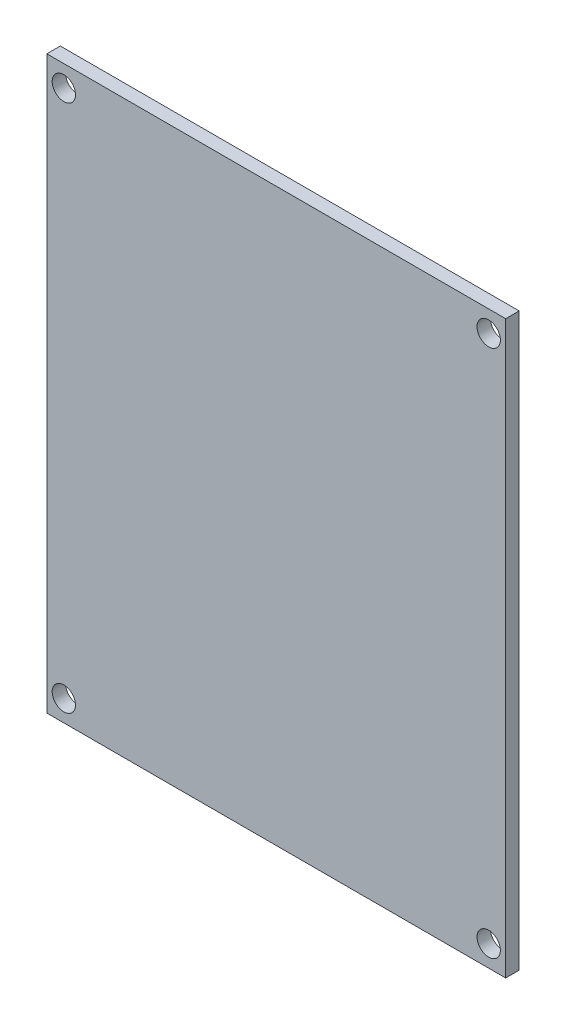
SolidWorks part; units mm, degrees
ref_plane "Front" through (0, 0, 0) normal (0, 0, 1) x (1, 0, 0)
ref_plane "Top" through (0, 0, 0) normal (0, 1, 0) x (1, 0, 0)
ref_plane "Right" through (0, 0, 0) normal (1, 0, 0) x (0, 0, -1)
sketch "Sketch1" plane through (0, 0, 0) normal (0, 0, 1) x (1, 0, 0)
  line L1 (-60, -67.25) -> (60, -67.25)
  line L2 (-60, -67.25) -> (-60, 67.25)
  line L3 (-60, 67.25) -> (60, 67.25)
  line L4 (60, -67.25) -> (60, 67.25)
  line L5 (-60, -67.25) -> (60, 67.25) construction
  line L6 (-60, 67.25) -> (60, -67.25) construction
  point P0 (0, 0)
  dimension "D1" = 134.5
  dimension "D2" = 120
extrude "Boss-Extrude1" add sketch "Sketch1" along normal blind 3.175
sketch "Sketch2" plane through (0, 0, 3.175) normal (0, 0, 1) x (1, 0, 0)
  line L1 (-48.0802, -67.25) -> (-48.0802, 67.25)
  line L3 (-48.0802, 67.25) -> (-60, 67.25)
  line L4 (-48.0802, 67.25) -> (-48.0802, -67.25)
  line L5 (-48.0802, -67.25) -> (-60, -67.25)
  line L6 (-60, 67.25) -> (-60, -67.25)
  line L7 (-48.0802, 67.25) -> (-60, -67.25) construction
  line L8 (-48.0802, -67.25) -> (-60, 67.25) construction
  circle A4 centre (56, -62.25) radius 2.75
  circle A5 centre (-44.0802, -62.25) radius 2.75
  circle A6 centre (56, 62.25) radius 2.75
  circle A7 centre (-44.0802, 62.25) radius 2.75
  point P5 (-54.0401, 0)
  line M2 (60, 67.25) -> (-60, 67.25)
  line M3 (-60, 67.25) -> (-60, -67.25)
  line M4 (-60, -67.25) -> (60, -67.25)
extrude "Cut-Extrude1" cut sketch "Sketch2" against normal up to next contours L1 M4 M2 M3 | A7 | A4 | A5 | A6
